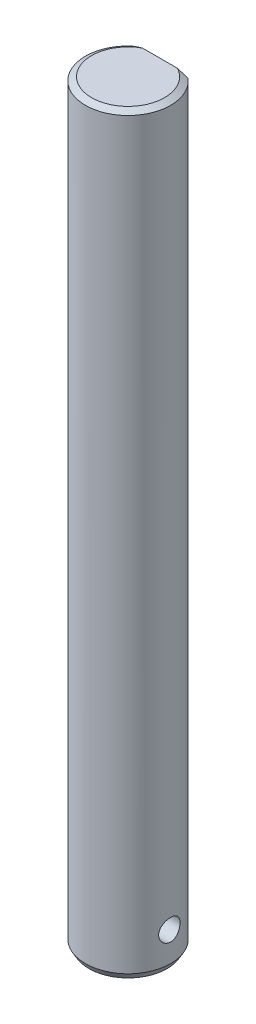
SolidWorks part; units mm, degrees
material "Titanium"
ref_plane "Front Plane" through (0, 0, 0) normal (0, 0, 1) x (1, 0, 0)
ref_plane "Top Plane" through (0, 0, 0) normal (0, 1, 0) x (1, 0, 0)
ref_plane "Right Plane" through (0, 0, 0) normal (1, 0, 0) x (0, 0, -1)
sketch "Sketch1" plane through (0, 0, 0) normal (0, 1, 0) x (1, 0, 0)
  circle A0 centre (0, 0) radius 6
  dimension "D1" = 12
extrude "Boss-Extrude1" add sketch "Sketch1" along normal blind 106
sketch "Sketch2" plane through (0, 106, 0) normal (0, 1, 0) x (1, 0, 0)
  line L1 (-6.1082, 8.2821) -> (6.3592, 8.2821)
  line L2 (-6.1082, 8.2821) -> (-6.1082, 4.5)
  line L3 (-6.1082, 4.5) -> (6.3592, 4.5)
  line L4 (6.3592, 8.2821) -> (6.3592, 4.5)
  dimension "D1" = 4.5
extrude "Cut-Extrude1" cut sketch "Sketch2" against normal blind 10
sketch "Sketch3" plane through (0, 0, 0) normal (1, 0, 0) x (0, 0, -1)
  circle A0 centre (0, 5) radius 1.5
  dimension "D1" = 3
  dimension "D2" = 5
extrude "Cut-Extrude2" cut sketch "Sketch3" against normal mid plane 100
chamfer "Chamfer1" distance 0.5 angle 60 2 edges at (0, 0, 6) (0, 106, 6)
